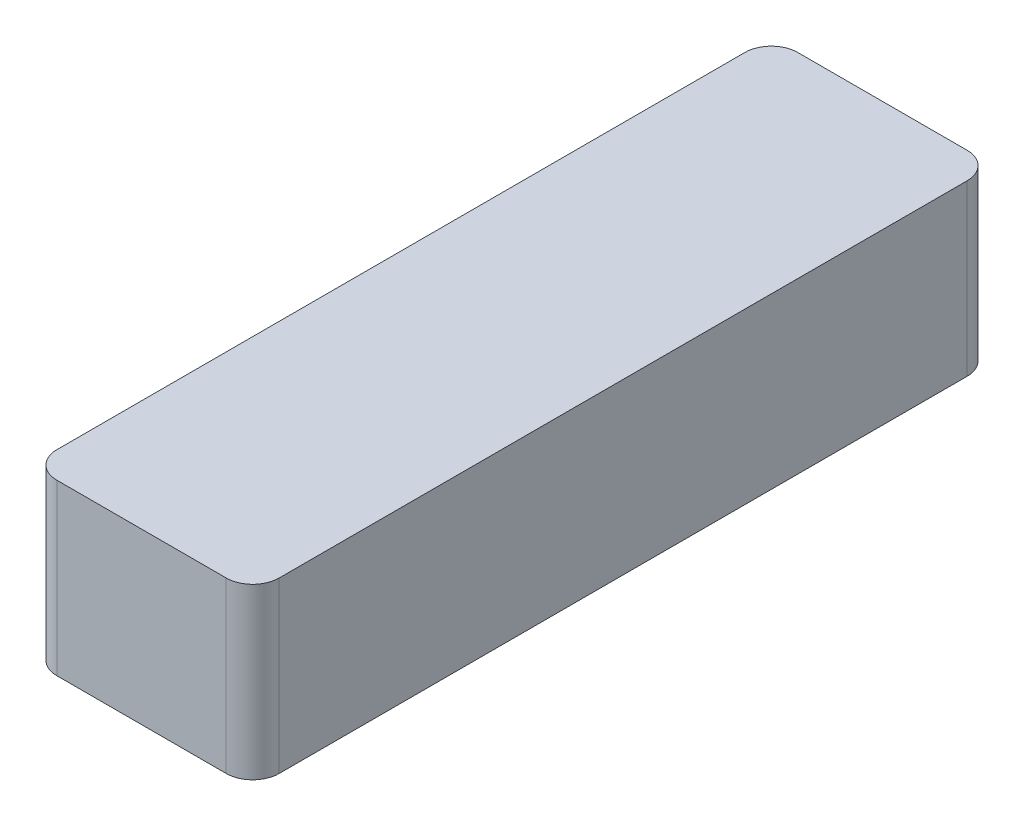
SolidWorks part; units mm, degrees
ref_plane "Ön Düzlem" through (0, 0, 0) normal (0, 0, 1) x (1, 0, 0)
ref_plane "Üst Düzlem" through (0, 0, 0) normal (0, 1, 0) x (1, 0, 0)
ref_plane "Sağ Düzlem" through (0, 0, 0) normal (1, 0, 0) x (0, 0, -1)
sketch "Çizim1" plane through (0, 0, 0) normal (0, 0, 1) x (1, 0, 0)
  line L1 (-21, -16) -> (21, -16)
  line L2 (-21, -16) -> (-21, 16)
  line L3 (-21, 16) -> (21, 16)
  line L4 (21, -16) -> (21, 16)
  line L5 (0, 16) -> (0, -16) construction
  line L6 (-21, 0) -> (21, 0) construction
  point P0 (0, 0)
  dimension "D1" = 42
  dimension "D2" = 32
extrude "Yükseklik-Ekstrüzyon1" add sketch "Çizim1" along normal blind 140
fillet "Radyus1" radius 5 4 edges at (-21, 0, 0) (21, 0, 0) (-21, 0, 140) (21, 0, 140)
